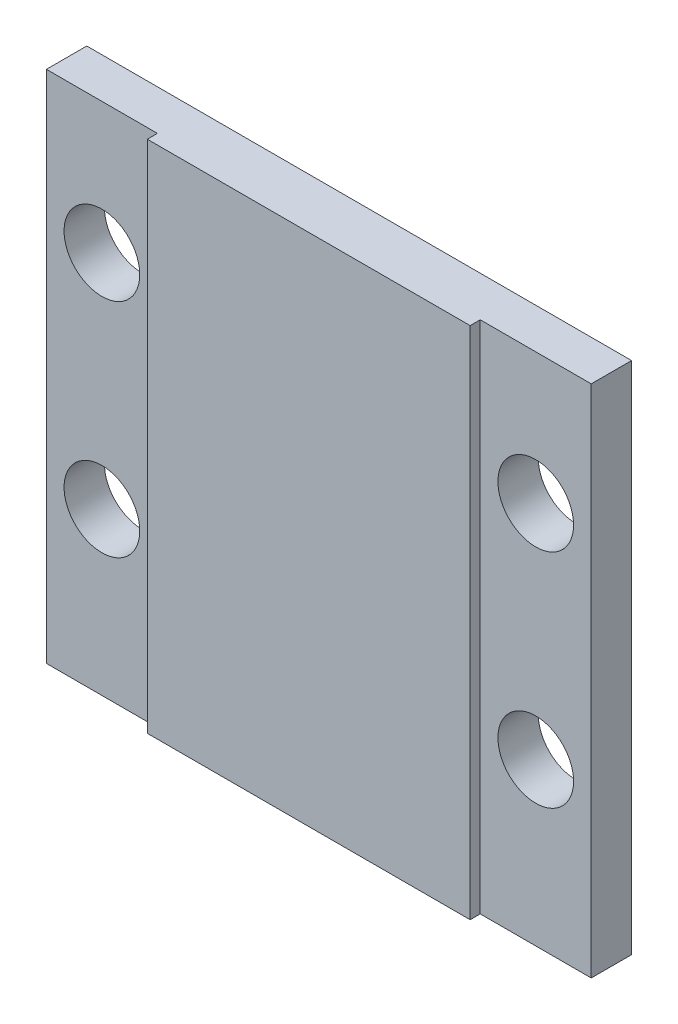
SolidWorks part; units mm, degrees
ref_plane "Alzado" through (0, 0, 0) normal (0, 0, 1) x (1, 0, 0)
ref_plane "Planta" through (0, 0, 0) normal (0, 1, 0) x (1, 0, 0)
ref_plane "Vista lateral" through (0, 0, 0) normal (1, 0, 0) x (0, 0, -1)
sketch "Croquis1" plane through (0, 0, 0) normal (0, 0, 1) x (1, 0, 0)
  line L1 (-27, 25.5) -> (27, 25.5)
  line L2 (-27, 25.5) -> (-27, -25.5)
  line L3 (-27, -25.5) -> (27, -25.5)
  line L4 (27, 25.5) -> (27, -25.5)
  line L5 (-27, 25.5) -> (27, -25.5) construction
  line L6 (-27, -25.5) -> (27, 25.5) construction
  circle A0 centre (-21.5, 12.5) radius 3.75
  circle A1 centre (21.5, 12.5) radius 3.75
  circle A2 centre (21.5, -9.5) radius 3.75
  circle A3 centre (-21.5, -9.5) radius 3.75
  point P0 (0, 0)
  dimension "D3" = 21.5
  dimension "D6" = 21.5
  dimension "D7" = 22
  dimension "D8" = 13
  dimension "D9" = 22
  dimension "D10" = 13
  dimension "D11" = 7.5
  dimension "D12" = 7.5
  dimension "D13" = 7.5
  dimension "D14" = 7.5
  dimension "D1" = 54
  dimension "D2" = 51
  dimension "D4" = 21.5
  dimension "D5" = 21.5
extrude "Saliente-Extruir1" add sketch "Croquis1" against normal blind 4
sketch "Croquis2" plane through (0, 0, 0) normal (0, 0, 1) x (1, 0, 0)
  line L0 (-27, -25.5) -> (27, -25.5) construction
  line L1 (-16, 25.5) -> (16, 25.5)
  line L2 (-16, 25.5) -> (-16, -25.5)
  line L3 (-16, -25.5) -> (16, -25.5)
  line L4 (16, 25.5) -> (16, -25.5)
  line L5 (-16, 25.5) -> (16, -25.5) construction
  line L6 (-16, -25.5) -> (16, 25.5) construction
  point P0 (0, 0)
  dimension "D1" = 32
extrude "Saliente-Extruir2" add sketch "Croquis2" along normal blind 1
